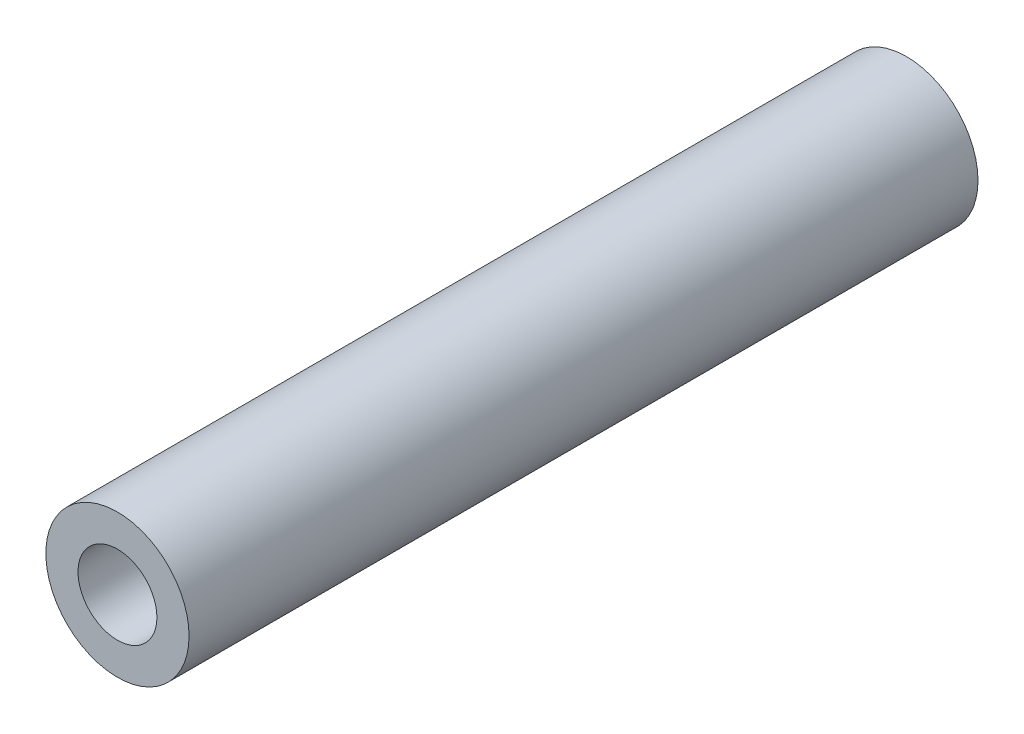
SolidWorks part; units mm, degrees
ref_plane "Front Plane" through (0, 0, 0) normal (1, 0, 0) x (0, 1, 0)
ref_plane "Top Plane" through (0, 0, 0) normal (0, 0, 1) x (0, 1, 0)
ref_plane "Right Plane" through (0, 0, 0) normal (0, 1, 0) x (-1, 0, 0)
sketch "Sketch1" plane through (0, 0, 0) normal (0, 0, 1) x (0, 1, 0)
  circle A0 centre (0, 0) radius 4.6101
  circle A1 centre (0, 0) radius 2.54
  dimension "D1" = 9.2202
  dimension "D2" = 5.08
extrude "Boss-Extrude1" add sketch "Sketch1" along normal blind 50.8
